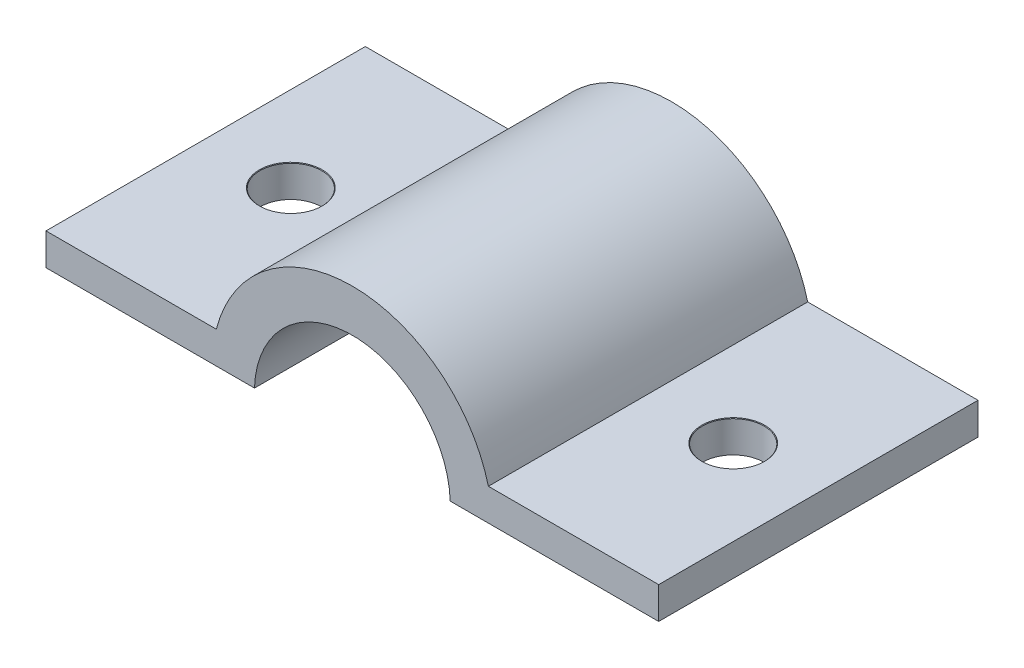
SolidWorks part; units mm, degrees
ref_plane "Front Plane" through (0, 0, 0) normal (0, 0, 1) x (1, 0, 0)
ref_plane "Top Plane" through (0, 0, 0) normal (0, 1, 0) x (1, 0, 0)
ref_plane "Right Plane" through (0, 0, 0) normal (1, 0, 0) x (0, 0, -1)
sketch "Sketch1" plane through (0, 0, 0) normal (0, 0, 1) x (1, 0, 0)
  line L0 (-14.3904, 0) -> (-4.5976, 0)
  line L1 (4.5976, 0) -> (14.3904, 0)
  line L7 (-14.3904, 0) -> (-14.3904, 1.5)
  line L8 (6.3904, 1.5) -> (14.3904, 1.5)
  line L9 (-14.3904, 1.5) -> (-6.3904, 1.5)
  line L14 (14.3904, 1.5) -> (14.3904, 0)
  arc A0 (-4.5976, 0) -> (4.5976, 0) centre (0, -0.15) cw
  arc A2 (-6.3904, 1.5) -> (6.3904, 1.5) centre (0, -0.15) cw
  dimension "D2" = 4.6
  dimension "D1" = 2
  dimension "D3" = 8
  dimension "D4" = 1.5
  dimension "D5" = 0.15
extrude "Boss-Extrude1" add sketch "Sketch1" along normal blind 15
hole_wizard "M2.5 Clearance Hole1" positions "Sketch3" profile "Sketch4" hole size "M2.5" standard "ANSI Metric" end condition through all
sketch "Sketch3" plane through (0, 1.5, 0) normal (0, 1, 0) x (1, 0, 0)
  line L0 (-6.3904, 0) -> (-14.3904, 0) construction
  line L1 (-14.3904, -15) -> (-14.3904, 0) construction
  line L2 (14.3904, 0) -> (6.3904, 0) construction
  point P0 (-10.3904, -7.5)
  point P2 (10.3904, -7.5)
  point P8 (-10.3904, 0)
  point P11 (-14.3904, -7.5)
  point P15 (10.3904, 0)
sketch "Sketch4" plane through (-10.3904, 1.5, 7.5) normal (1, 0, 0) x (0, 0, 1)
  line L0 (0, 0) -> (0, 1.5)
  line L1 (0, 1.5) -> (1.45, 1.5)
  line L2 (1.45, 1.5) -> (1.45, 0.025)
  line L3 (1.45, 0.025) -> (1.475, 0)
  line L5 (1.475, 0) -> (0, 0)
  line L6 (-1.45, 0.025) -> (-1.475, 0) construction
  line L11 (0, -6.35) -> (0, 107.95) construction
  dimension "Thru Hole Dia." = 2.9
  dimension "Thru Hole Depth" = 1.5
  dimension "Near C'Sink Dia." = 2.95
  dimension "Near C'Sink Angle" = 90
sketch "Sketch5" plane through (0, 1.5, 0) normal (0, 1, 0) x (1, 0, 0)
  line L1 (-7.7654, -9.0155) -> (-7.7654, -5.9845)
  line L2 (-7.7654, -5.9845) -> (-10.3904, -4.4689)
  line L3 (-10.3904, -4.4689) -> (-13.0154, -5.9845)
  line L4 (-13.0154, -5.9845) -> (-13.0154, -9.0155)
  line L5 (-13.0154, -9.0155) -> (-10.3904, -10.5311)
  line L6 (-10.3904, -10.5311) -> (-7.7654, -9.0155)
  circle A0 centre (-10.3904, -7.5) radius 2.625 construction
  dimension "D1" = 5.25
